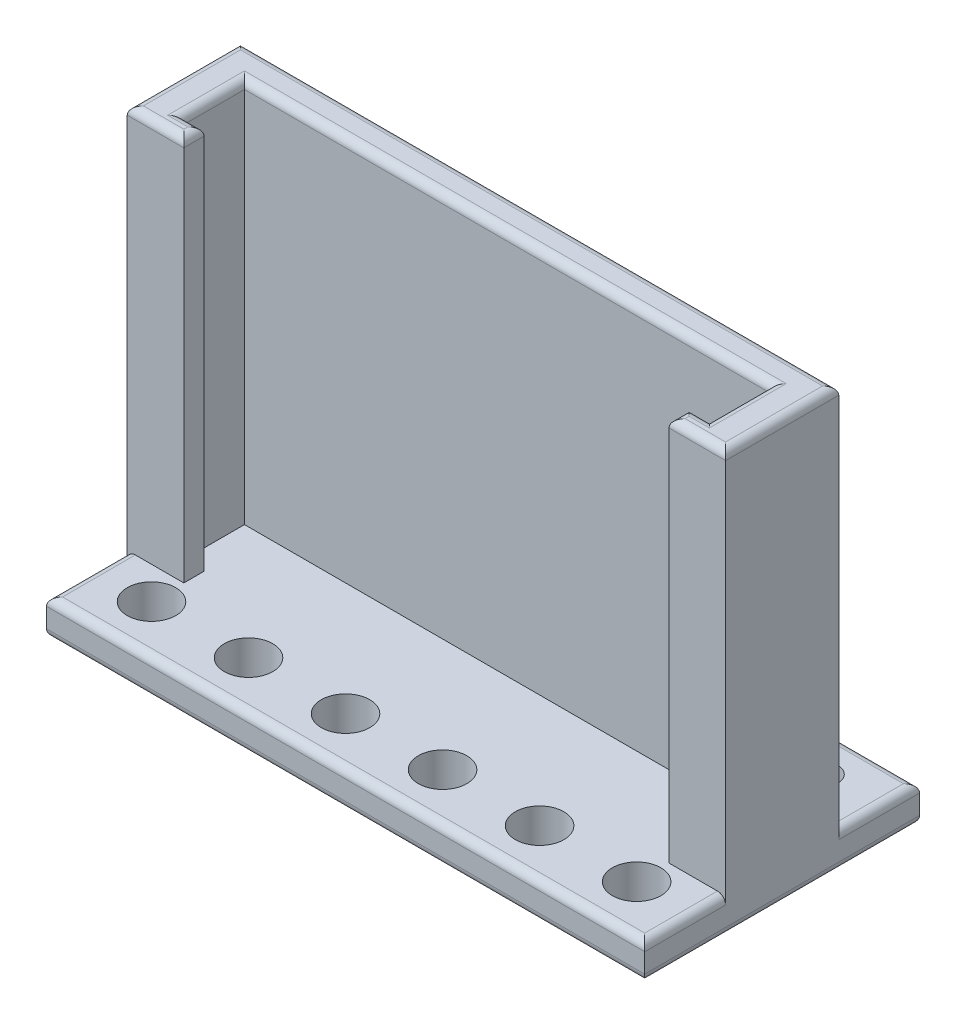
SolidWorks part; units mm, degrees
material "Copper"
ref_plane "Front Plane" through (0, 0, 0) normal (0, 0, 1) x (1, 0, 0)
ref_plane "Top Plane" through (0, 0, 0) normal (0, 1, 0) x (1, 0, 0)
ref_plane "Right Plane" through (0, 0, 0) normal (1, 0, 0) x (0, 0, -1)
sketch "Sketch2" plane through (0, 0, 0) normal (0, 0, 1) x (1, 0, 0)
  line L1 (0, 0) -> (93.98, 0)
  line L2 (0, 0) -> (0, 66.04)
  line L3 (0, 66.04) -> (93.98, 66.04)
  line L4 (93.98, 0) -> (93.98, 66.04)
  dimension "D1" = 93.98
  dimension "D2" = 66.04
extrude "Boss-Extrude1" add sketch "Sketch2" along normal blind 17.78
sketch "Sketch3" plane through (0, 0, 17.78) normal (0, 0, 1) x (1, 0, 0)
  line L0 (93.98, 0) -> (93.98, 66.04) construction
  line L1 (0, 0) -> (93.98, 0)
  line L2 (0, 0) -> (0, 5.588)
  line L3 (0, 5.588) -> (93.98, 5.588)
  line L4 (93.98, 0) -> (93.98, 5.588)
  dimension "D1" = 5.588
extrude "Boss-Extrude2" add sketch "Sketch3" along normal blind 12.7
sketch "Sketch4" plane through (0, 66.04, 0) normal (0, 1, 0) x (1, 0, 0)
  line L5 (0, -5.08) -> (5.715, -5.08) construction
  line L6 (0, -17.78) -> (0, 0) construction
  line L7 (93.98, -17.78) -> (93.98, 0) construction
  line L8 (0, -14.605) -> (5.715, -14.605) construction
  line L9 (5.715, -5.08) -> (88.265, -5.08)
  line L10 (5.715, -5.08) -> (5.715, -14.605)
  line L11 (5.715, -14.605) -> (88.265, -14.605)
  line L12 (88.265, -5.08) -> (88.265, -14.605)
  line L13 (88.265, -14.605) -> (93.98, -14.605) construction
  line L14 (88.265, -5.08) -> (93.98, -5.08) construction
  line L15 (93.98, -17.78) -> (0, -17.78) construction
  line L16 (8.89, -14.605) -> (85.09, -14.605)
  line L17 (8.89, -14.605) -> (8.89, -17.78)
  line L18 (8.89, -17.78) -> (85.09, -17.78)
  line L19 (85.09, -14.605) -> (85.09, -17.78)
  point P18 (46.99, -5.08)
  point P19 (46.99, -17.78)
  dimension "D1" = 82.55
  dimension "D2" = 9.525
  dimension "D3" = 3.175
  dimension "D4" = 76.2
extrude "Cut-Extrude1" cut sketch "Sketch4" against normal up to surface (60.452 mm away) contours L12 L9 L10 L11 | L18 L19 L16 L17 up to face at (46.99, 5.588, 24.13)
sketch "Sketch5" plane through (0, 0, 0) normal (0, 0, -1) x (-1, 0, 0)
  line L0 (0, 66.04) -> (0, 0) construction
  line L1 (-93.98, 0) -> (0, 0)
  line L2 (-93.98, 0) -> (-93.98, 5.588)
  line L3 (-93.98, 5.588) -> (0, 5.588)
  line L4 (0, 0) -> (0, 5.588)
  dimension "D1" = 5.588
extrude "Boss-Extrude3" add sketch "Sketch5" along normal blind 12.7
sketch "Sketch6" plane through (0, 5.588, 0) normal (0, 1, 0) x (1, 0, 0)
  line L0 (93.98, -22.86) -> (85.09, -22.86) construction
  line L3 (93.98, 6.35) -> (85.09, 6.35) construction
  line L4 (93.98, 12.7) -> (93.98, 0) construction
  line L5 (0, 12.7) -> (0, 0) construction
  line L6 (85.09, 6.35) -> (8.89, 6.35) construction
  line L7 (8.89, 6.35) -> (0, 6.35) construction
  line L8 (8.89, -22.86) -> (0, -22.86) construction
  line L9 (93.98, -30.48) -> (93.98, -17.78) construction
  line L10 (0, -30.48) -> (0, -17.78) construction
  circle A0 centre (8.89, 6.35) radius 2.413
  circle A1 centre (21.59, 6.35) radius 2.413
  circle A2 centre (34.29, 6.35) radius 2.413
  circle A3 centre (46.99, 6.35) radius 2.413
  circle A4 centre (59.69, 6.35) radius 2.413
  circle A5 centre (72.39, 6.35) radius 2.413
  circle A6 centre (85.09, 6.35) radius 2.413
  circle A7 centre (8.89, -22.86) radius 3.81
  circle A8 centre (24.13, -22.86) radius 3.81
  circle A9 centre (39.37, -22.86) radius 3.81
  circle A10 centre (54.61, -22.86) radius 3.81
  circle A11 centre (69.85, -22.86) radius 3.81
  circle A12 centre (85.09, -22.86) radius 3.81
  point P2 (80.9807, -22.86)
  point P3 (0, 0)
  point P26 (8.89, -27.305)
  point P37 (0, 0)
  point P39 (68.3558, -61.4587)
  point P40 (0, 0)
  point P42 (0, 0)
  point P43 (0, 0)
  point P47 (0, 0)
  dimension "D1" = 4.826
  dimension "D4" = 7.62
  dimension "D3" = 12.7
  dimension "D6" = 15.24
  dimension "D7" = 5.08
  dimension "D2" = 7
  dimension "D5" = 6
extrude "Cut-Extrude2" cut sketch "Sketch6" against normal through all
fillet "Fillet1" radius 1.27 12 edges at (86.6775, 66.04, 14.605) (88.265, 66.04, 9.8425) (46.99, 66.04, 5.08) (5.715, 66.04, 9.8425) (7.3025, 66.04, 14.605) (8.89, 66.04, 16.1925) (4.445, 66.04, 17.78) (0, 66.04, 8.89) (46.99, 66.04, 0) (93.98, 66.04, 8.89) (89.535, 66.04, 17.78) (85.09, 66.04, 16.1925)
fillet "Fillet2" radius 1.27 6 edges at (93.98, 5.588, -6.35) (46.99, 5.588, -12.7) (0, 5.588, -6.35) (93.98, 5.588, 24.13) (46.99, 5.588, 30.48) (0, 5.588, 24.13)
fillet "Fillet3" radius 1.27 4 edges at (46.99, 0, -12.7) (93.98, 0, 8.89) (46.99, 0, 30.48) (0, 0, 8.89)
